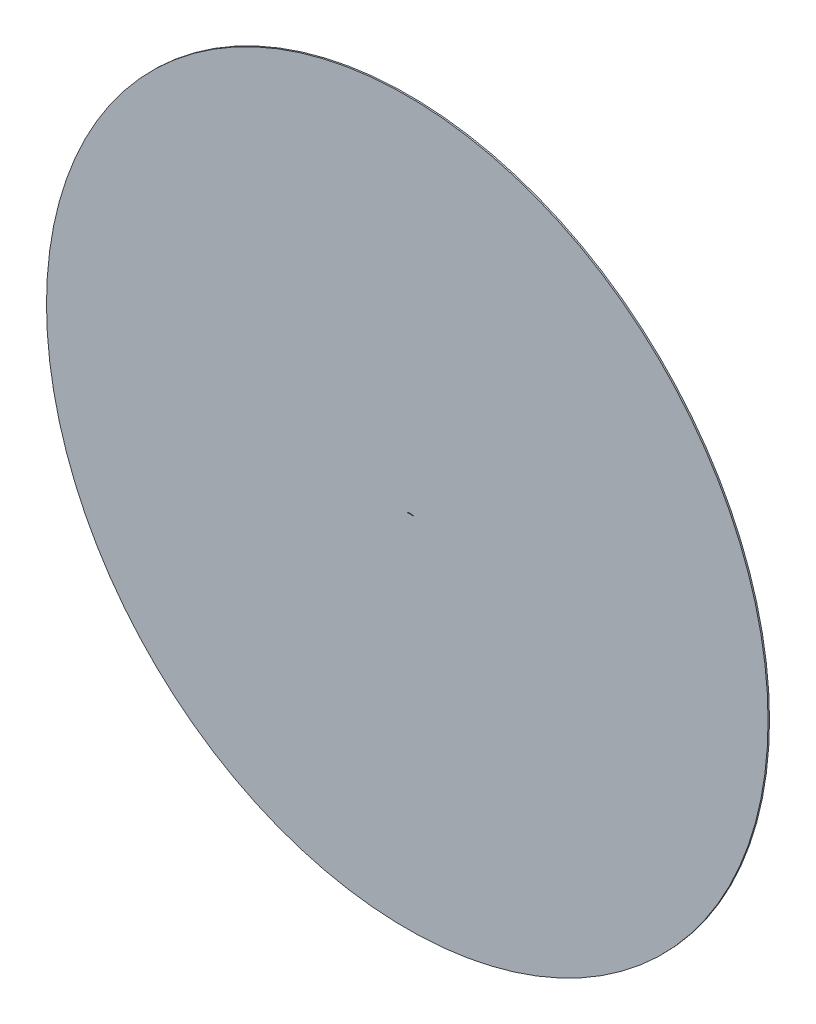
SolidWorks part; units mm, degrees
ref_plane "Front Plane" through (0, 0, 0) normal (0, 0, 1) x (1, 0, 0)
ref_plane "Top Plane" through (0, 0, 0) normal (0, 1, 0) x (1, 0, 0)
ref_plane "Right Plane" through (0, 0, 0) normal (1, 0, 0) x (0, 0, -1)
curve "Curve2"
  spline degree 3 poles (297.8112, 0.1193, 0) (300.551, -0.0526, 0) (297.8569, 0.2924, 0) (295.7235, 0.7269, 0) (290.6793, 1.6795, 0) (284.636, 2.8974, 0) (276.8799, 4.3445, 0) (267.8204, 5.9528, 0) (257.4554, 7.7422, 0) (245.9678, 9.7066, 0) (233.506, 11.7913, 0) (220.2517, 13.9739, 0) (206.382, 16.1817, 0) (192.0879, 18.3685, 0) (177.5587, 20.4566, 0) (162.9701, 22.3599, 0) (148.4557, 23.9245, 0) (134.1246, 25.0697, 0) (120.0622, 25.7341, 0) (106.3483, 25.898, 0) (93.0557, 25.5554, 0) (80.2659, 24.7293, 0) (68.0722, 23.5171, 0) (56.5872, 21.9624, 0) (45.926, 20.1178, 0) (36.196, 18.0185, 0) (27.4877, 15.7195, 0) (19.8856, 13.2615, 0) (13.4453, 10.6996, 0) (8.2441, 8.0983, 0) (4.2211, 5.5402, 0) (1.6313, 3.0904, 0) (-0.1756, 0.951, 0) (0.2436, -1.5643, 0) (2.945, -2.7565, 0) (6.5373, -3.9802, 0) (11.8704, -4.8918, 0) (18.6191, -5.6203, 0) (26.8722, -6.0904, 0) (36.5215, -6.3388, 0) (47.5018, -6.3568, 0) (59.7032, -6.1935, 0) (73.0044, -5.8696, 0) (87.2611, -5.4198, 0) (102.3136, -4.8787, 0) (117.9871, -4.2822, 0) (134.0968, -3.664, 0) (150.4464, -3.0481, 0) (166.8333, -2.4637, 0) (183.0523, -1.9282, 0) (198.9012, -1.4505, 0) (214.1814, -1.048, 0) (228.6992, -0.7139, 0) (242.2712, -0.4576, 0) (254.7178, -0.2669, 0) (265.8917, -0.1451, 0) (275.6125, -0.059, 0) (283.8949, 0.0156, 0) (290.3056, 0.1166, 0) (295.5963, 0.09, 0) (297.8112, 0.1193, 0) (300.551, -0.0526, 0) (297.8569, 0.2924, 0) knots -0.014753 -0.006696 -0.001699 0 0.001687 0.006616 0.014466 0.024924 0.0378 0.052988 0.070317 0.089535 0.11036 0.132501 0.155651 0.179484 0.203673 0.227895 0.251892 0.275517 0.298645 0.321169 0.343005 0.364075 0.384236 0.403305 0.421106 0.437475 0.452283 0.465415 0.476784 0.48634 0.494069 0.499999 0.50417 0.506997 0.51109 0.517452 0.526209 0.537392 0.550962 0.566841 0.58491 0.604997 0.626901 0.650394 0.675202 0.701035 0.727593 0.75455 0.781563 0.808299 0.834421 0.859605 0.883532 0.905896 0.926412 0.944812 0.960858 0.974374 0.985247 0.993304 0.998301 1 1.001687 1.006616 1.014466 periodic
sketch "Sketch2" plane through (0, 0, 0) normal (0, 0, 1) x (1, 0, 0)
  circle A0 centre (0, 0) radius 15000
  spline S0 degree 3 poles (297.8112, 0.1193) (300.551, -0.0526) (297.8569, 0.2924) (295.7235, 0.7269) (290.6793, 1.6795) (284.636, 2.8974) (276.8799, 4.3445) (267.8204, 5.9528) (257.4554, 7.7422) (245.9678, 9.7066) (233.506, 11.7913) (220.2517, 13.9739) (206.382, 16.1817) (192.0879, 18.3685) (177.5587, 20.4566) (162.9701, 22.3599) (148.4557, 23.9245) (134.1246, 25.0697) (120.0622, 25.7341) (106.3483, 25.898) (93.0557, 25.5554) (80.2659, 24.7293) (68.0722, 23.5171) (56.5872, 21.9624) (45.926, 20.1178) (36.196, 18.0185) (27.4877, 15.7195) (19.8856, 13.2615) (13.4453, 10.6996) (8.2441, 8.0983) (4.2211, 5.5402) (1.6313, 3.0904) (-0.1756, 0.951) (0.2436, -1.5643) (2.945, -2.7565) (6.5373, -3.9802) (11.8704, -4.8918) (18.6191, -5.6203) (26.8722, -6.0904) (36.5215, -6.3388) (47.5018, -6.3568) (59.7032, -6.1935) (73.0044, -5.8696) (87.2611, -5.4198) (102.3136, -4.8787) (117.9871, -4.2822) (134.0968, -3.664) (150.4464, -3.0481) (166.8333, -2.4637) (183.0523, -1.9282) (198.9012, -1.4505) (214.1814, -1.048) (228.6992, -0.7139) (242.2712, -0.4576) (254.7178, -0.2669) (265.8917, -0.1451) (275.6125, -0.059) (283.8949, 0.0156) (290.3056, 0.1166) (295.5963, 0.09) (297.8112, 0.1193) (300.551, -0.0526) (297.8569, 0.2924) knots -0.014753 -0.006696 -0.001699 0 0.001687 0.006616 0.014466 0.024924 0.0378 0.052988 0.070317 0.089535 0.11036 0.132501 0.155651 0.179484 0.203673 0.227895 0.251892 0.275517 0.298645 0.321169 0.343005 0.364075 0.384236 0.403305 0.421106 0.437475 0.452283 0.465415 0.476784 0.48634 0.494069 0.499999 0.50417 0.506997 0.51109 0.517452 0.526209 0.537392 0.550962 0.566841 0.58491 0.604997 0.626901 0.650394 0.675202 0.701035 0.727593 0.75455 0.781563 0.808299 0.834421 0.859605 0.883532 0.905896 0.926412 0.944812 0.960858 0.974374 0.985247 0.993304 0.998301 1 1.001687 1.006616 1.014466 only from (300, 0) to (300, 0) construction
  spline S1 degree 3 poles (297.8112, 0.1193) (300.551, -0.0526) (297.8569, 0.2924) (295.7235, 0.7269) (290.6793, 1.6795) (284.636, 2.8974) (276.8799, 4.3445) (267.8204, 5.9528) (257.4554, 7.7422) (245.9678, 9.7066) (233.506, 11.7913) (220.2517, 13.9739) (206.382, 16.1817) (192.0879, 18.3685) (177.5587, 20.4566) (162.9701, 22.3599) (148.4557, 23.9245) (134.1246, 25.0697) (120.0622, 25.7341) (106.3483, 25.898) (93.0557, 25.5554) (80.2659, 24.7293) (68.0722, 23.5171) (56.5872, 21.9624) (45.926, 20.1178) (36.196, 18.0185) (27.4877, 15.7195) (19.8856, 13.2615) (13.4453, 10.6996) (8.2441, 8.0983) (4.2211, 5.5402) (1.6313, 3.0904) (-0.1756, 0.951) (0.2436, -1.5643) (2.945, -2.7565) (6.5373, -3.9802) (11.8704, -4.8918) (18.6191, -5.6203) (26.8722, -6.0904) (36.5215, -6.3388) (47.5018, -6.3568) (59.7032, -6.1935) (73.0044, -5.8696) (87.2611, -5.4198) (102.3136, -4.8787) (117.9871, -4.2822) (134.0968, -3.664) (150.4464, -3.0481) (166.8333, -2.4637) (183.0523, -1.9282) (198.9012, -1.4505) (214.1814, -1.048) (228.6992, -0.7139) (242.2712, -0.4576) (254.7178, -0.2669) (265.8917, -0.1451) (275.6125, -0.059) (283.8949, 0.0156) (290.3056, 0.1166) (295.5963, 0.09) (297.8112, 0.1193) (300.551, -0.0526) (297.8569, 0.2924) knots -0.014753 -0.006696 -0.001699 0 0.001687 0.006616 0.014466 0.024924 0.0378 0.052988 0.070317 0.089535 0.11036 0.132501 0.155651 0.179484 0.203673 0.227895 0.251892 0.275517 0.298645 0.321169 0.343005 0.364075 0.384236 0.403305 0.421106 0.437475 0.452283 0.465415 0.476784 0.48634 0.494069 0.499999 0.50417 0.506997 0.51109 0.517452 0.526209 0.537392 0.550962 0.566841 0.58491 0.604997 0.626901 0.650394 0.675202 0.701035 0.727593 0.75455 0.781563 0.808299 0.834421 0.859605 0.883532 0.905896 0.926412 0.944812 0.960858 0.974374 0.985247 0.993304 0.998301 1 1.001687 1.006616 1.014466 only from (300, 0) to (300, 0)
  dimension "D1" = 30000
extrude "Boss-Extrude1" add sketch "Sketch2" along normal mid plane 60
